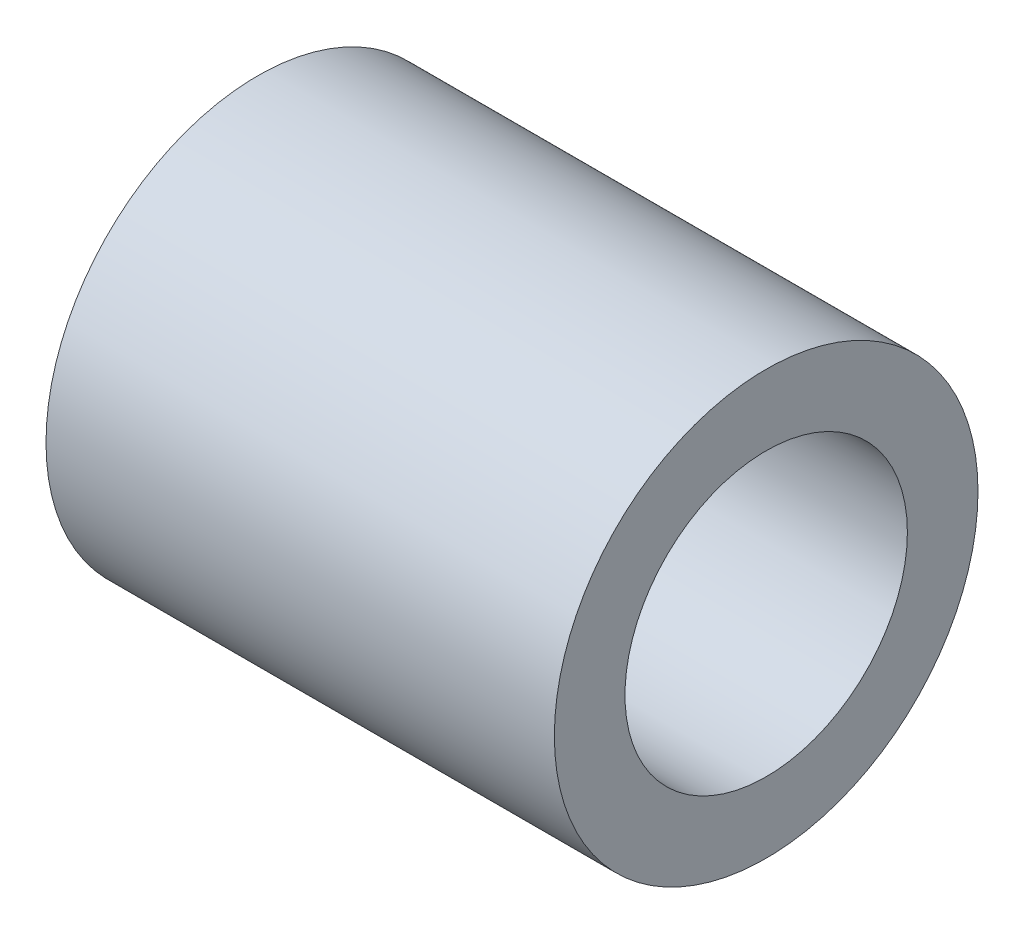
SolidWorks part; units mm, degrees
ref_plane "Front Plane" through (0, 0, 0) normal (0, 0, 1) x (1, 0, 0)
ref_plane "Top Plane" through (0, 0, 0) normal (0, 1, 0) x (1, 0, 0)
ref_plane "Right Plane" through (0, 0, 0) normal (1, 0, 0) x (0, 0, -1)
sketch "Sketch1" plane through (0, 0, 0) normal (1, 0, 0) x (0, 0, -1)
  circle A0 centre (0, 0) radius 5
  circle A1 centre (0, 0) radius 7.5
  dimension "D1" = 15
  dimension "D2" = 10
extrude "Boss-Extrude1" add sketch "Sketch1" along normal blind 18
